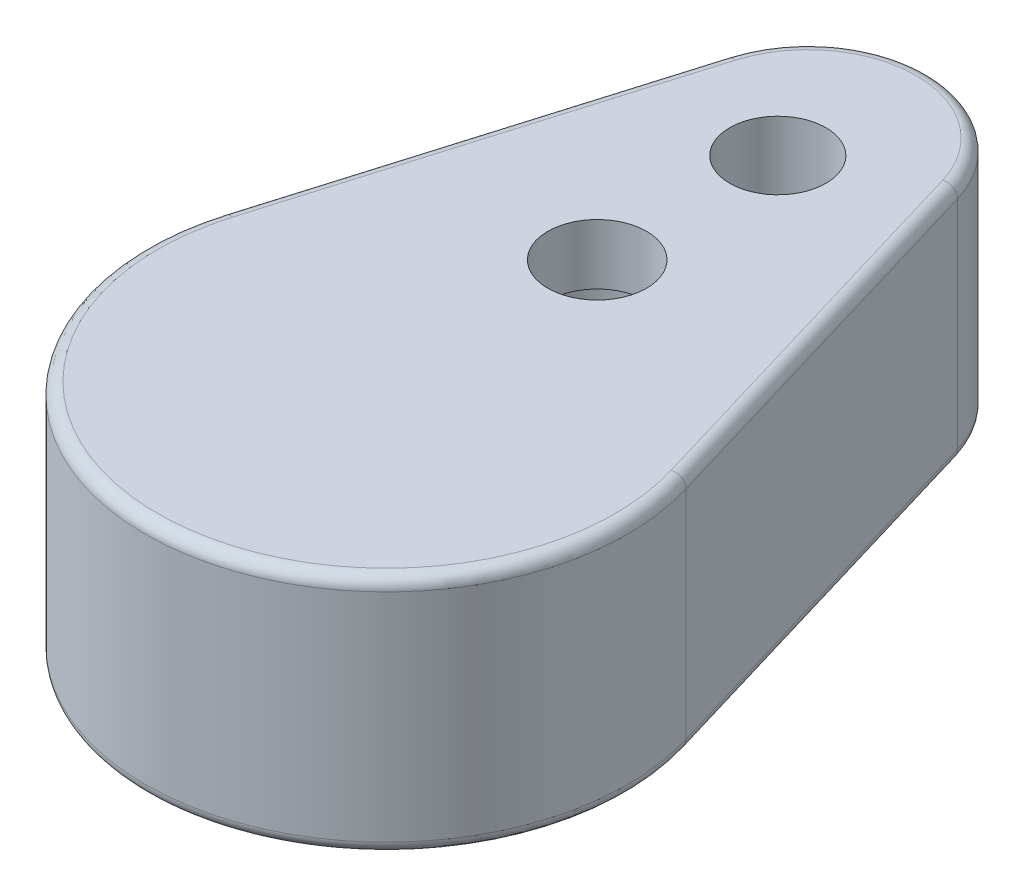
SolidWorks part; units mm, degrees
ref_plane "Front Plane" through (0, 0, 0) normal (0, 0, 1) x (1, 0, 0)
ref_plane "Top Plane" through (0, 0, 0) normal (0, 1, 0) x (1, 0, 0)
ref_plane "Right Plane" through (0, 0, 0) normal (1, 0, 0) x (0, 0, -1)
sketch "Sketch1" plane through (0, 0, 0) normal (0, 1, 0) x (1, 0, 0)
  line L0 (-9.5831, 20.3571) -> (-19.1663, -11.7857)
  line L1 (9.5831, 20.3571) -> (19.1663, -11.7857)
  arc A0 (9.5831, 20.3571) -> (-9.5831, 20.3571) centre (0, 17.5) ccw
  arc A1 (-19.1663, -11.7857) -> (19.1663, -11.7857) centre (0, -17.5) ccw
  dimension "D1" = 20
  dimension "D2" = 40
  dimension "D3" = 35
  dimension "D4" = 17.5
extrude "Boss-Extrude1" add sketch "Sketch1" along normal blind 20
fillet "Fillet1" radius 1 8 edges at (0, 0, -27.5) (14.3747, 0, -4.2857) (0, 0, 37.5) (0, 20, -27.5) (14.3747, 20, -4.2857) (0, 20, 37.5) (-14.3747, 0, -4.2857) (-14.3747, 20, -4.2857)
sketch "Sketch2" plane through (0, 20, 0) normal (0, 1, 0) x (1, 0, 0)
  circle A0 centre (0, 15) radius 4
  dimension "D1" = 15
  dimension "D2" = 8
extrude "Cut-Extrude1" cut sketch "Sketch2" against normal blind 15
sketch "Sketch3" plane through (0, 0, 0) normal (0, -1, 0) x (1, 0, 0)
  circle A0 centre (0, 0) radius 5
  dimension "D1" = 10
extrude "Cut-Extrude2" cut sketch "Sketch3" against normal blind 15
sketch "Sketch4" plane through (0, 15, 0) normal (0, -1, 0) x (1, 0, 0)
  circle A0 centre (0, 0) radius 4.1
  circle A1 centre (0, -15) radius 3.1
  dimension "D1" = 8.2
  dimension "D2" = 6.2
  dimension "D3" = 15
extrude "Cut-Extrude3" cut sketch "Sketch4" against normal through all both and the other way through all
